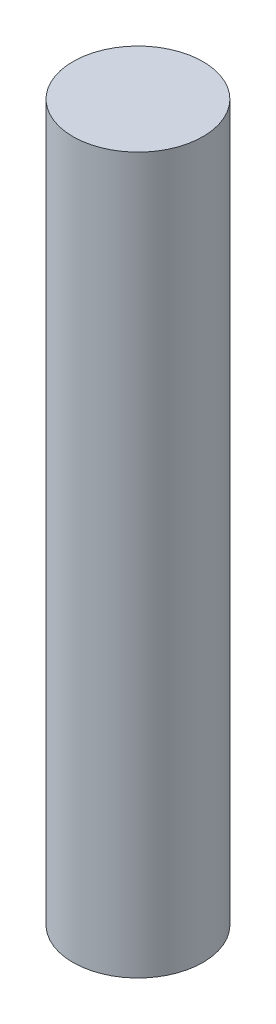
SolidWorks part; units mm, degrees
ref_plane "Front Plane" through (0, 0, 0) normal (0, 0, 1) x (1, 0, 0)
ref_plane "Top Plane" through (0, 0, 0) normal (0, 1, 0) x (1, 0, 0)
ref_plane "Right Plane" through (0, 0, 0) normal (1, 0, 0) x (0, 0, -1)
sketch "BODY" plane through (0, 0, 0) normal (0, 1, 0) x (1, 0, 0)
  circle A0 centre (0, 0) radius 2
extrude "Body Extrude" add sketch "BODY" along normal blind 22
